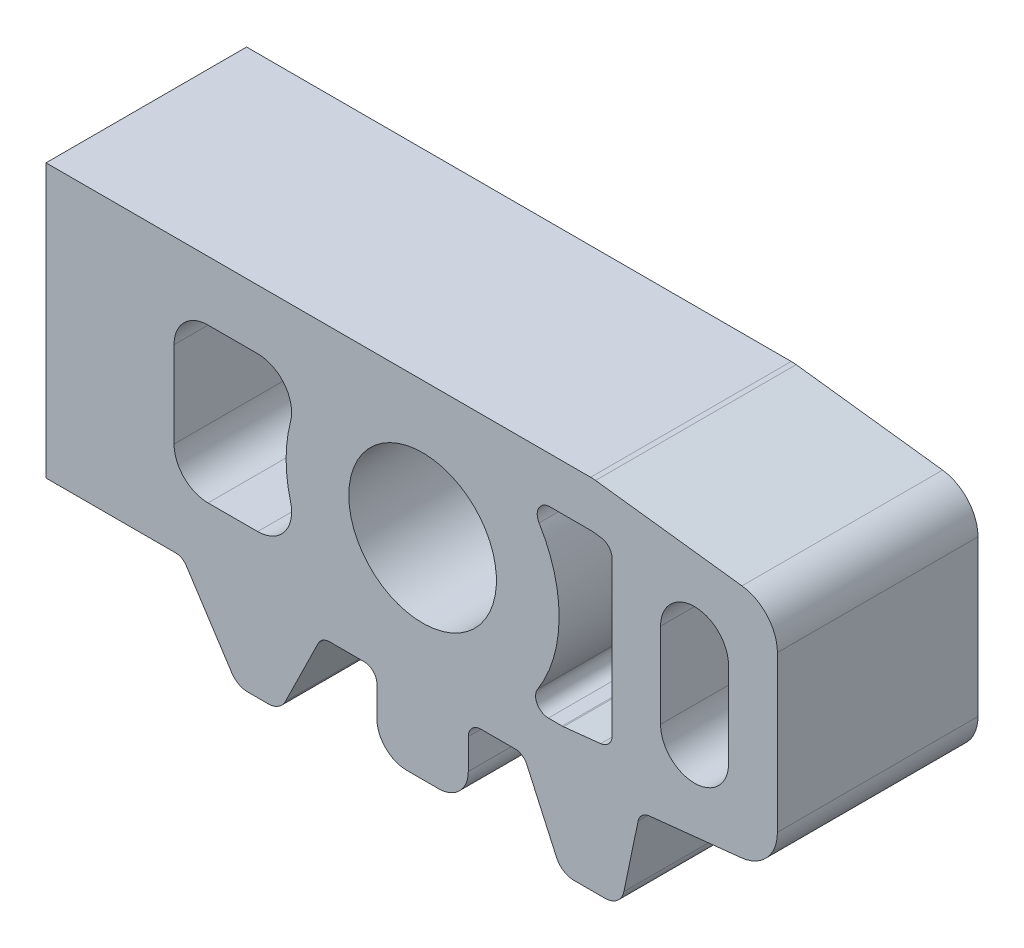
SolidWorks part; units mm, degrees
material "Custom Plastic"
ref_plane "X-Y Datum" through (0, 0, 0) normal (0, 0, 1) x (1, 0, 0)
ref_plane "X-Z Datum" through (0, 0, 0) normal (0, 1, 0) x (1, 0, 0)
ref_plane "Y-Z Datum" through (0, 0, 0) normal (1, 0, 0) x (0, 0, -1)
sketch "Sketch1" plane through (0, 0, 0) normal (0, 0, 1) x (1, 0, 0)
  line L134 (51.3102, -26.8547) -> (52.0377, -26.7777)
  line L135 (52.0377, -26.7777) -> (53.2334, -26.651)
  line L136 (43.3558, -27.6974) -> (51.3102, -26.8547)
  line L137 (42.1334, -27.8269) -> (43.3558, -27.6974)
  line L138 (37.578, -27.8481) -> (41.7321, -27.8481)
  line L139 (43.9578, 27.0701) -> (38.0645, 27.0701)
  line L140 (50.4094, 27.0701) -> (43.9578, 27.0701)
  line L141 (51.2118, 27) -> (50.8764, 27.0414)
  line L142 (51.9393, 26.9101) -> (51.2118, 27)
  line L143 (53.299, 26.7422) -> (51.9393, 26.9101)
  line L144 (56.642, -22.8622) -> (56.642, 22.9609)
  line L145 (51.3102, -26.8547) -> (52.0377, -26.7777)
  line L146 (52.0377, -26.7777) -> (53.2334, -26.651)
  line L147 (43.3558, -27.6974) -> (51.3102, -26.8547)
  line L148 (42.1334, -27.8269) -> (43.3558, -27.6974)
  line L149 (37.578, -27.8481) -> (41.7321, -27.8481)
  line L150 (43.9578, 27.0701) -> (38.0645, 27.0701)
  line L151 (50.4094, 27.0701) -> (43.9578, 27.0701)
  line L152 (51.2118, 27) -> (50.8764, 27.0414)
  line L153 (51.9393, 26.9101) -> (51.2118, 27)
  line L154 (53.299, 26.7422) -> (51.9393, 26.9101)
  line L155 (56.642, -22.8622) -> (56.642, 22.9609)
  line L166 (-49.3097, 23.0187) -> (-64.1279, 23.0187)
  line L167 (-74.2879, 12.8587) -> (-74.2879, -12.8588)
  line L168 (-64.1279, -23.0188) -> (-49.3097, -23.0188)
  line L169 (-49.3097, 23.0187) -> (-64.1279, 23.0187)
  line L170 (-74.2879, 12.8587) -> (-74.2879, -12.8588)
  line L171 (-64.1279, -23.0188) -> (-49.3097, -23.0188)
  line L467 (71.12, 12.7) -> (71.12, -12.7)
  line L468 (91.44, -12.7) -> (91.44, 12.7)
  line L469 (71.12, 12.7) -> (71.12, -12.7)
  line L470 (91.44, -12.7) -> (91.44, 12.7)
  line L480 (-112.5601, 40.7987) -> (-112.5601, -40.7988)
  line L481 (-112.5601, -40.7988) -> (-105.6454, -40.7988)
  line L482 (-105.6454, -40.7988) -> (-78.273, -40.7988)
  line L483 (-78.273, -40.7988) -> (-73.8188, -40.7988)
  line L484 (-70.6238, -42.5333) -> (-57.044, -63.4382)
  line L485 (-52.2514, -66.04) -> (-46.1455, -66.04)
  line L486 (-41.0176, -62.848) -> (-31.2159, -42.9267)
  line L487 (-27.7973, -40.7988) -> (-17.4625, -40.7988)
  line L488 (-13.6525, -44.6088) -> (-13.6525, -53.6575)
  line L489 (-4.7625, -62.5475) -> (4.7625, -62.5475)
  line L490 (13.6525, -53.6575) -> (13.6525, -44.6088)
  line L491 (17.4625, -40.7988) -> (27.6548, -40.7988)
  line L492 (31.1255, -43.0371) -> (40.0215, -62.6825)
  line L493 (45.2276, -66.04) -> (54.568, -66.04)
  line L494 (60.163, -61.4901) -> (64.4078, -41.1056)
  line L495 (67.7364, -38.0936) -> (95.2511, -35.1786)
  line L496 (106.045, -23.1808) -> (106.045, 23.3289)
  line L497 (95.4587, 35.303) -> (51.6928, 40.7078)
  line L498 (50.2141, 40.7987) -> (-70.3716, 40.7987)
  line L499 (-70.3716, 40.7987) -> (-78.273, 40.7987)
  line L500 (-78.273, 40.7987) -> (-105.6454, 40.7987)
  line L501 (-105.6454, 40.7987) -> (-112.5601, 40.7987)
  line L502 (-112.5601, 40.7987) -> (-112.5601, -40.7988)
  line L503 (-112.5601, -40.7988) -> (-105.6454, -40.7988)
  line L504 (-105.6454, -40.7988) -> (-78.273, -40.7988)
  line L505 (-78.273, -40.7988) -> (-73.8188, -40.7988)
  line L506 (-70.6238, -42.5333) -> (-57.044, -63.4382)
  line L507 (-52.2514, -66.04) -> (-46.1455, -66.04)
  line L508 (-41.0176, -62.848) -> (-31.2159, -42.9267)
  line L509 (-27.7973, -40.7988) -> (-17.4625, -40.7988)
  line L510 (-13.6525, -44.6088) -> (-13.6525, -53.6575)
  line L511 (-4.7625, -62.5475) -> (4.7625, -62.5475)
  line L512 (13.6525, -53.6575) -> (13.6525, -44.6088)
  line L513 (17.4625, -40.7988) -> (27.6548, -40.7988)
  line L514 (31.1255, -43.0371) -> (40.0215, -62.6825)
  line L515 (45.2276, -66.04) -> (54.568, -66.04)
  line L516 (60.163, -61.4901) -> (64.4078, -41.1056)
  line L517 (67.7364, -38.0936) -> (95.2511, -35.1786)
  line L518 (106.045, -23.1808) -> (106.045, 23.3289)
  line L519 (95.4587, 35.303) -> (51.6928, 40.7078)
  line L520 (50.2141, 40.7987) -> (-70.3716, 40.7987)
  line L521 (-70.3716, 40.7987) -> (-78.273, 40.7987)
  line L522 (-78.273, 40.7987) -> (-105.6454, 40.7987)
  line L523 (-105.6454, 40.7987) -> (-112.5601, 40.7987)
  arc A90 (34.3685, -21.9851) -> (34.8135, 21.2735) centre (0, 0) ccw
  arc A91 (53.2334, -26.651) -> (56.642, -22.8622) centre (52.832, -22.8622) ccw
  arc A92 (41.7321, -27.8481) -> (42.1334, -27.8269) centre (41.7321, -24.0381) ccw
  arc A93 (34.3685, -21.9851) -> (37.578, -27.8481) centre (37.578, -24.0381) ccw
  arc A94 (38.0645, 27.0701) -> (34.8135, 21.2735) centre (38.0645, 23.2601) ccw
  arc A95 (50.8764, 27.0414) -> (50.4094, 27.0701) centre (50.4094, 23.2601) ccw
  arc A96 (56.642, 22.9609) -> (53.299, 26.7422) centre (52.832, 22.9609) ccw
  arc A97 (34.3685, -21.9851) -> (34.8135, 21.2735) centre (0, 0) ccw
  arc A98 (53.2334, -26.651) -> (56.642, -22.8622) centre (52.832, -22.8622) ccw
  arc A99 (41.7321, -27.8481) -> (42.1334, -27.8269) centre (41.7321, -24.0381) ccw
  arc A100 (34.3685, -21.9851) -> (37.578, -27.8481) centre (37.578, -24.0381) ccw
  arc A101 (38.0645, 27.0701) -> (34.8135, 21.2735) centre (38.0645, 23.2601) ccw
  arc A102 (50.8764, 27.0414) -> (50.4094, 27.0701) centre (50.4094, 23.2601) ccw
  arc A103 (56.642, 22.9609) -> (53.299, 26.7422) centre (52.832, 22.9609) ccw
  arc A141 (-39.4785, 10.295) -> (-39.4785, -10.295) centre (0, 0) ccw
  arc A142 (-39.4785, 10.295) -> (-49.3097, 23.0187) centre (-49.3097, 12.8587) ccw
  arc A143 (-64.1279, 23.0187) -> (-69.1229, 21.7061) centre (-64.1279, 12.8587) ccw
  arc A144 (-69.1229, 21.7061) -> (-74.2879, 12.8587) centre (-64.1279, 12.8588) ccw
  arc A145 (-74.2879, -12.8588) -> (-69.1229, -21.7061) centre (-64.1279, -12.8587) ccw
  arc A146 (-69.1229, -21.7061) -> (-64.1279, -23.0188) centre (-64.1279, -12.8588) ccw
  arc A147 (-49.3097, -23.0188) -> (-39.4785, -10.295) centre (-49.3097, -12.8588) ccw
  arc A148 (-39.4785, 10.295) -> (-39.4785, -10.295) centre (0, 0) ccw
  arc A149 (-39.4785, 10.295) -> (-49.3097, 23.0187) centre (-49.3097, 12.8587) ccw
  arc A150 (-64.1279, 23.0187) -> (-69.1229, 21.7061) centre (-64.1279, 12.8587) ccw
  arc A151 (-69.1229, 21.7061) -> (-74.2879, 12.8587) centre (-64.1279, 12.8588) ccw
  arc A152 (-74.2879, -12.8588) -> (-69.1229, -21.7061) centre (-64.1279, -12.8587) ccw
  arc A153 (-69.1229, -21.7061) -> (-64.1279, -23.0188) centre (-64.1279, -12.8588) ccw
  arc A154 (-49.3097, -23.0188) -> (-39.4785, -10.295) centre (-49.3097, -12.8588) ccw
  circle A322 centre (0, 0) radius 22.0663
  circle A323 centre (0, 0) radius 22.0663
  arc A336 (-71.7505, -41.409) -> (-73.8188, -40.7988) centre (-73.8188, -44.6088) ccw
  arc A337 (-70.6238, -42.5333) -> (-71.7505, -41.409) centre (-73.8188, -44.6088) ccw
  arc A338 (-57.044, -63.4382) -> (-52.2514, -66.04) centre (-52.2514, -60.325) ccw
  arc A339 (-46.1455, -66.04) -> (-41.0176, -62.848) centre (-46.1455, -60.325) ccw
  arc A340 (-27.7973, -40.7988) -> (-31.2159, -42.9267) centre (-27.7973, -44.6088) ccw
  arc A341 (-13.6525, -44.6088) -> (-17.4625, -40.7988) centre (-17.4625, -44.6088) ccw
  arc A342 (-13.6525, -53.6575) -> (-4.7625, -62.5475) centre (-4.7625, -53.6575) ccw
  arc A343 (4.7625, -62.5475) -> (13.6525, -53.6575) centre (4.7625, -53.6575) ccw
  arc A344 (17.4625, -40.7988) -> (13.6525, -44.6088) centre (17.4625, -44.6088) ccw
  arc A345 (31.1255, -43.0371) -> (27.6548, -40.7988) centre (27.6548, -44.6088) ccw
  arc A346 (40.0215, -62.6825) -> (45.2276, -66.04) centre (45.2276, -60.325) ccw
  arc A347 (54.568, -66.04) -> (60.163, -61.4901) centre (54.568, -60.325) ccw
  arc A348 (67.7364, -38.0936) -> (64.4078, -41.1056) centre (68.1378, -41.8824) ccw
  arc A349 (95.2511, -35.1786) -> (106.045, -23.1808) centre (93.98, -23.1808) ccw
  arc A350 (106.045, 23.3289) -> (95.4587, 35.303) centre (93.98, 23.3289) ccw
  arc A351 (51.6928, 40.7078) -> (50.2141, 40.7987) centre (50.2141, 28.7337) ccw
  arc A352 (-71.7505, -41.409) -> (-73.8188, -40.7988) centre (-73.8188, -44.6088) ccw
  arc A353 (-70.6238, -42.5333) -> (-71.7505, -41.409) centre (-73.8188, -44.6088) ccw
  arc A354 (-57.044, -63.4382) -> (-52.2514, -66.04) centre (-52.2514, -60.325) ccw
  arc A355 (-46.1455, -66.04) -> (-41.0176, -62.848) centre (-46.1455, -60.325) ccw
  arc A356 (-27.7973, -40.7988) -> (-31.2159, -42.9267) centre (-27.7973, -44.6088) ccw
  arc A357 (-13.6525, -44.6088) -> (-17.4625, -40.7988) centre (-17.4625, -44.6088) ccw
  arc A358 (-13.6525, -53.6575) -> (-4.7625, -62.5475) centre (-4.7625, -53.6575) ccw
  arc A359 (4.7625, -62.5475) -> (13.6525, -53.6575) centre (4.7625, -53.6575) ccw
  arc A360 (17.4625, -40.7988) -> (13.6525, -44.6088) centre (17.4625, -44.6088) ccw
  arc A361 (31.1255, -43.0371) -> (27.6548, -40.7988) centre (27.6548, -44.6088) ccw
  arc A362 (40.0215, -62.6825) -> (45.2276, -66.04) centre (45.2276, -60.325) ccw
  arc A363 (54.568, -66.04) -> (60.163, -61.4901) centre (54.568, -60.325) ccw
  arc A364 (67.7364, -38.0936) -> (64.4078, -41.1056) centre (68.1378, -41.8824) ccw
  arc A365 (95.2511, -35.1786) -> (106.045, -23.1808) centre (93.98, -23.1808) ccw
  arc A366 (106.045, 23.3289) -> (95.4587, 35.303) centre (93.98, 23.3289) ccw
  arc A367 (51.6928, 40.7078) -> (50.2141, 40.7987) centre (50.2141, 28.7337) ccw
  arc A373 (71.12, -12.7) -> (71.435, -15.2102) centre (81.28, -12.7) ccw
  arc A374 (71.435, 15.2102) -> (71.12, 12.7) centre (81.28, 12.7) ccw
  arc A375 (91.44, 12.7) -> (71.435, 15.2102) centre (81.28, 12.7) ccw
  arc A376 (71.435, -15.2102) -> (91.44, -12.7) centre (81.28, -12.7) ccw
  arc A377 (71.12, -12.7) -> (71.435, -15.2102) centre (81.28, -12.7) ccw
  arc A378 (71.435, 15.2102) -> (71.12, 12.7) centre (81.28, 12.7) ccw
  arc A379 (91.44, 12.7) -> (71.435, 15.2102) centre (81.28, 12.7) ccw
  arc A380 (71.435, -15.2102) -> (91.44, -12.7) centre (81.28, -12.7) ccw
  dimension "D1" = 2.54
  dimension "D2" = 2.54
  dimension "D3" = 2.54
  dimension "D4" = 2.54
  dimension "D5" = 2.54
extrude "Boss-Extrude1" add sketch "Sketch1" along normal offset from surface 2.54 and the other way offset from surface (28.5212 mm away) 2.54
